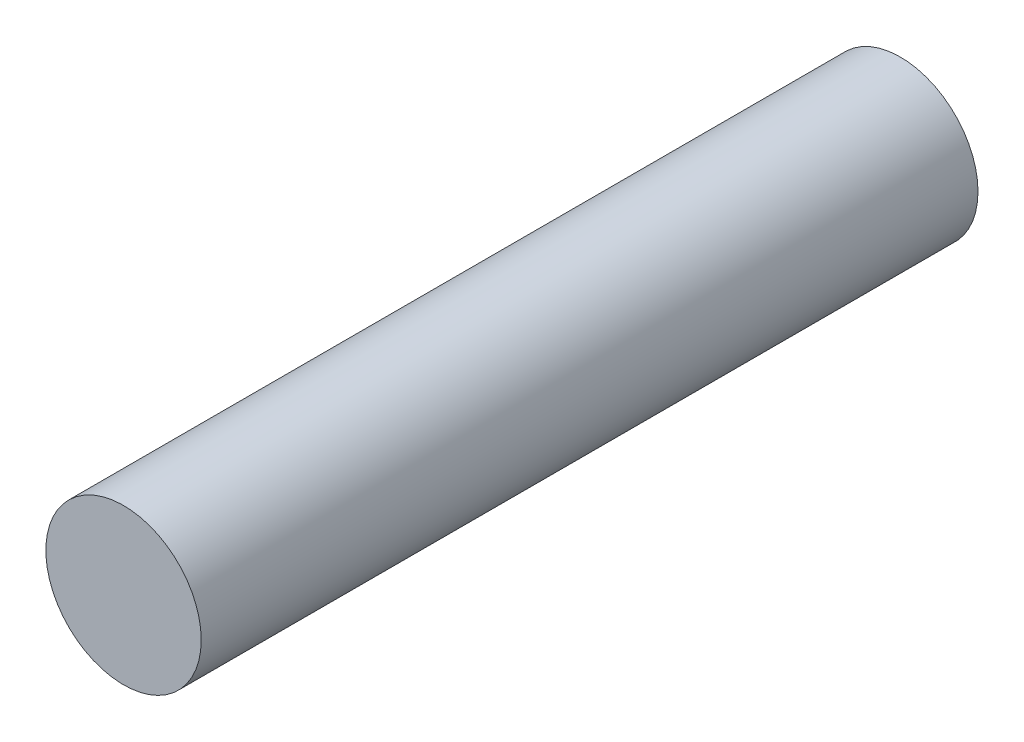
SolidWorks part; units mm, degrees
ref_plane "Front Plane" through (0, 0, 0) normal (0, 0, 1) x (1, 0, 0)
ref_plane "Top Plane" through (0, 0, 0) normal (0, 1, 0) x (1, 0, 0)
ref_plane "Right Plane" through (0, 0, 0) normal (1, 0, 0) x (0, 0, -1)
sketch "Sketch2" plane through (0, 0, 0) normal (0, 1, 0) x (1, 0, 0)
  line L0 (0, 0) -> (0, 5)
  dimension "D1" = 5
revolve "Revolve-Thin1" add sketch "Sketch2" angle 360 about L0 wall 0.5
